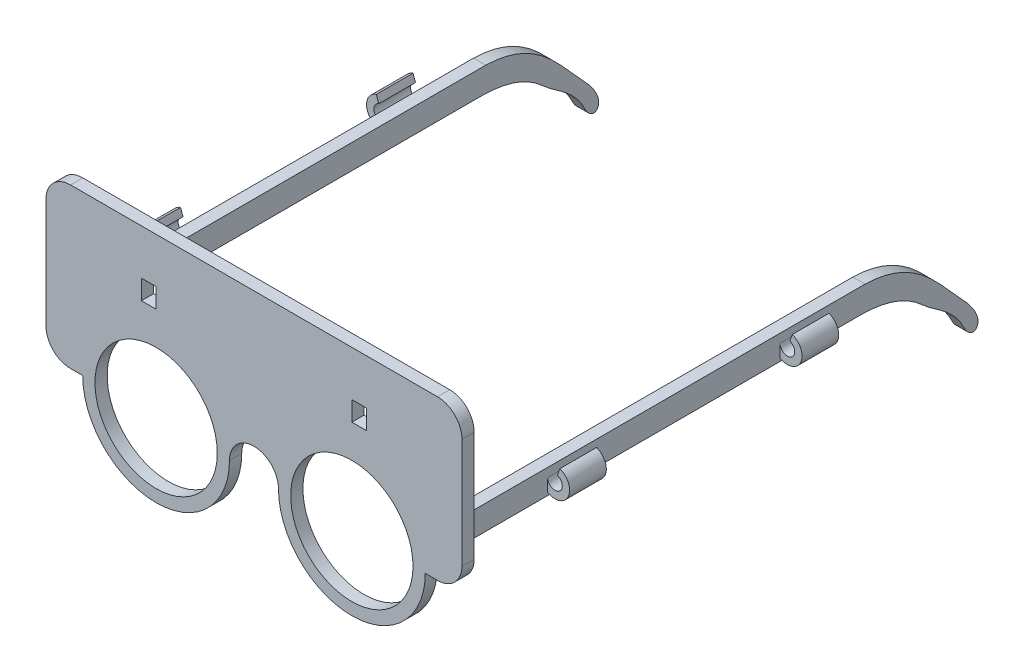
SolidWorks part; units mm, degrees
ref_plane "Front Plane" through (0, 0, 0) normal (0, 0, 1) x (1, 0, 0)
ref_plane "Top Plane" through (0, 0, 0) normal (0, 1, 0) x (1, 0, 0)
ref_plane "Right Plane" through (0, 0, 0) normal (1, 0, 0) x (0, 0, -1)
sketch "Sketch1" plane through (0, 0, 0) normal (0, 0, 1) x (1, 0, 0)
  line L0 (0, 0) -> (0, 99.9751) construction
  line L1 (-65, 60) -> (65, 60) construction
  line L2 (-65, 60) -> (-65, 33.5) construction
  line L3 (-65, 33.5) -> (65, 33.5) construction
  line L4 (65, 60) -> (65, 33.5) construction
  line L5 (-85, 10) -> (-85, 55)
  line L14 (-75, 65) -> (75, 65)
  line L15 (75, 12.5) -> (80, 12.5)
  line L16 (75, 12.5) -> (75, 22.5)
  line L17 (-80, 22.5) -> (-75, 22.5)
  line L18 (-70, 0) -> (-75, 0)
  line L19 (85, 55) -> (85, 10)
  line L20 (80, 12.5) -> (80, 22.5)
  line L21 (-80, 12.5) -> (-75, 12.5)
  line L22 (75, 22.5) -> (80, 22.5)
  line L23 (-80, 22.5) -> (-80, 12.5)
  line L24 (75, 0) -> (70, 0)
  line L25 (-75, 22.5) -> (-75, 12.5)
  line L26 (-46, 38.5) -> (-40, 38.5)
  line L27 (-46, 38.5) -> (-46, 46.5)
  line L28 (-46, 46.5) -> (-40, 46.5)
  line L29 (-40, 38.5) -> (-40, 46.5)
  line L34 (46, 46.5) -> (40, 46.5)
  line L35 (40, 38.5) -> (40, 46.5)
  line L36 (46, 38.5) -> (40, 38.5)
  line L37 (46, 38.5) -> (46, 46.5)
  arc A4 (-70, 0) -> (-10, 0) centre (-40, 0) ccw
  arc A5 (10, 0) -> (-10, 0) centre (0, 0) ccw
  arc A7 (10, 0) -> (70, 0) centre (40, 0) ccw
  arc A8 (75, 65) -> (85, 55) centre (75, 55) cw
  arc A9 (85, 10) -> (75, 0) centre (75, 10) cw
  arc A10 (-85, 10) -> (-75, 0) centre (-75, 10) ccw
  arc A11 (-85, 55) -> (-75, 65) centre (-75, 55) cw
  circle A12 centre (-40, 0) radius 25
  circle A13 centre (40, 0) radius 25
  point P10 (0, 60)
  point P11 (0, 65)
  point P14 (85, 65)
  point P22 (-85, 0)
  point P29 (-85, 65)
  dimension "D1" = 60
  dimension "D2" = 60
  dimension "D3" = 5
  dimension "D5" = 15
  dimension "D6" = 20
  dimension "D7" = 8
  dimension "D18" = 10
  dimension "D19" = 50
  dimension "D20" = 50
  dimension "D4" = 12.5
  dimension "D8" = 65
  dimension "D9" = 170
  dimension "D10" = 12.5
  dimension "D11" = 5
  dimension "D12" = 5
  dimension "D13" = 5
  dimension "D14" = 40
  dimension "D15" = 26.5
  dimension "D16" = 130
  dimension "D17" = 5
  dimension "D21" = 6
  dimension "D22" = 10
  dimension "D23" = 10
  dimension "D24" = 40
  dimension "D25" = 5
extrude "Boss-Extrude1" add sketch "Sketch1" along normal blind 5
ref_plane "Plane1" through (77.5, 0, 0) normal (1, 0, 0) x (0, 0, -1)
sketch "Sketch3" plane through (77.5, 0, 0) normal (1, 0, 0) x (0, 0, -1)
  line L2 (-5, 22.5) -> (195, 22.5)
  line L3 (-5, 10) -> (-5, 55) construction
  line L4 (-5, 12.5) -> (-5, 22.5)
  line L5 (-5, 10) -> (0, 10) construction
  line L6 (162.7154, 12.5) -> (-5, 12.5)
  spline S0 degree 3 poles (162.7154, 22.5) (175.9733, 22.796) (189.7774, 14.2466) (201.2051, 0.3485) (209.8637, -8.1129) (211.1193, -13.8238) (209.9263, -17.2095) (206.497, -16.05) (201.73, -5.2147) (193.1198, -1.0009) (186.3595, 5.1886) (177.1929, 12.5) (162.7154, 12.5) knots 0 0 0 0 0.171436 0.266664 0.355542 0.377182 0.385126 0.429439 0.469195 0.74293 0.799432 1 1 1 1
  dimension "D3" = 167.7154
  dimension "D1" = 200
  dimension "D2" = 12.5
  dimension "D5" = 10
extrude "Boss-Extrude2" add sketch "Sketch3" along normal mid plane 5 contours S0 L2 L4 L6
mirror "Mirror1" about plane through (0, 0, 0) normal (1, 0, 0) of "Boss-Extrude2"
ref_plane "Plane3" through (0, 0, -50) normal (0, 0, 1) x (1, 0, 0)
sketch "Sketch6" plane through (0, 0, -50) normal (0, 0, 1) x (1, 0, 0)
  line L2 (80, -16.5113) -> (80, 22.5) construction
  line L3 (80, 12.5) -> (80, 22.5) construction
  line L4 (80, 12.5) -> (80, 22.5)
  line L5 (82, 16.0639) -> (85.2637, 25.2951) construction
  arc A0 (80, 13.6962) -> (85, 24.5492) centre (83, 18.8924) ccw
  arc A2 (80, 18.8924) -> (84, 21.7208) centre (83, 18.8924) ccw
  point P7 (0, 0)
  point P8 (84.4576, 23.2792)
  point P10 (87.065, 24.6334)
  point P12 (85.9113, 25.0212)
  dimension "D1" = 6
  dimension "D3" = 4
  dimension "D2" = 6
  dimension "D4" = 3
extrude "Boss-Extrude3" add sketch "Sketch6" along normal blind 15
ref_plane "Plane4" through (0, 0, -90) normal (0, 0, 1) x (1, 0, 0)
mirror "Mirror2" about plane through (0, 0, -90) normal (0, 0, 1) of "Boss-Extrude3" second plane through (0, 0, 0) second plane normal (1, 0, 0)
